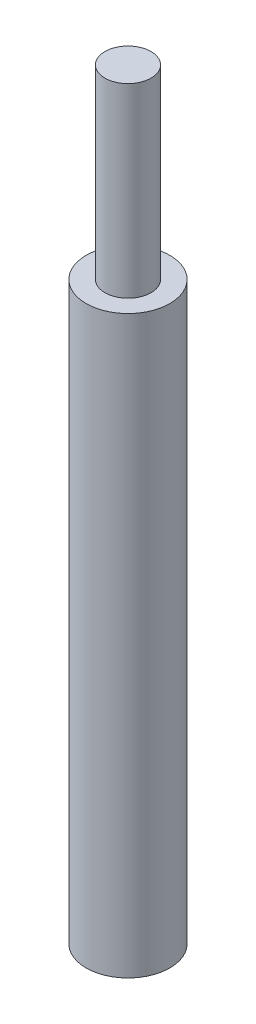
SolidWorks part; units mm, degrees
ref_plane "Front Plane" through (0, 0, 0) normal (0, 0, 1) x (1, 0, 0)
ref_plane "Top Plane" through (0, 0, 0) normal (0, 1, 0) x (1, 0, 0)
ref_plane "Right Plane" through (0, 0, 0) normal (1, 0, 0) x (0, 0, -1)
sketch "Sketch1" plane through (0, 0, 0) normal (0, 1, 0) x (1, 0, 0)
  circle A0 centre (0, 0) radius 7.1438
  dimension "D1" = 14.2875
extrude "Boss-Extrude1" add sketch "Sketch1" along normal blind 130.048
hole_wizard "M10x1.0 Tapped Hole1" positions "Sketch3" profile "Sketch2" tap size "M10x1.0" standard "Ansi Metric"
sketch "Sketch3" plane through (0, 0, 0) normal (0, -1, 0) x (1, 0, 0)
  point P1 (0, 0)
sketch "Sketch2" plane through (0, 0, 0) normal (1, 0, 0) x (0, 0, -1)
  line L0 (0, 0) -> (0, 17.7039)
  line L1 (0, 17.7039) -> (4.5, 15)
  line L2 (4.5, 15) -> (4.5, 0)
  line L5 (4.5, 0) -> (0, 0)
  line L10 (0, 17.7039) -> (-4.5, 15) construction
  line L11 (0, -6.35) -> (0, 107.95) construction
  dimension "Tap Drill Dia." = 9
  dimension "Tap Drill Depth" = 15
  dimension "Drill Angle" = 118
cosmetic thread "Hole Thread1" parameters "D1"=15, "D2"=10
sketch "Sketch4" plane through (0, 130.048, 0) normal (0, 1, 0) x (1, 0, 0)
  circle A0 centre (0, 0) radius 3.937
  circle A1 centre (0, 0) radius 7.1438
  dimension "D1" = 7.874
extrude "Cut-Extrude1" cut sketch "Sketch4" against normal blind 31.75
